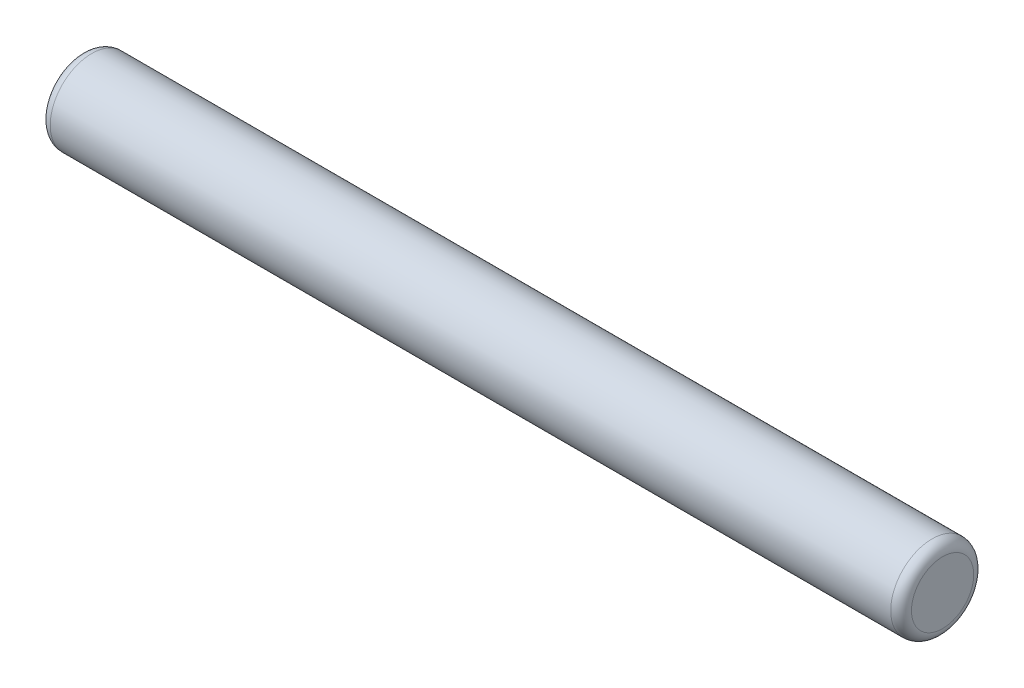
SolidWorks part; units mm, degrees
ref_plane "Front" through (0, 0, 0) normal (0, 0, 1) x (1, 0, 0)
ref_plane "Top" through (0, 0, 0) normal (0, 1, 0) x (1, 0, 0)
ref_plane "Right" through (0, 0, 0) normal (1, 0, 0) x (0, 0, -1)
sketch "Sketch1" plane through (0, 0, 0) normal (1, 0, 0) x (0, 0, -1)
  circle A0 centre (0, 0) radius 4
  dimension "D1" = 8
extrude "Boss-Extrude1" add sketch "Sketch1" along normal blind 83
fillet "Fillet1" radius 1 2 edges at (83, 0, -4) (0, 0, -4)
